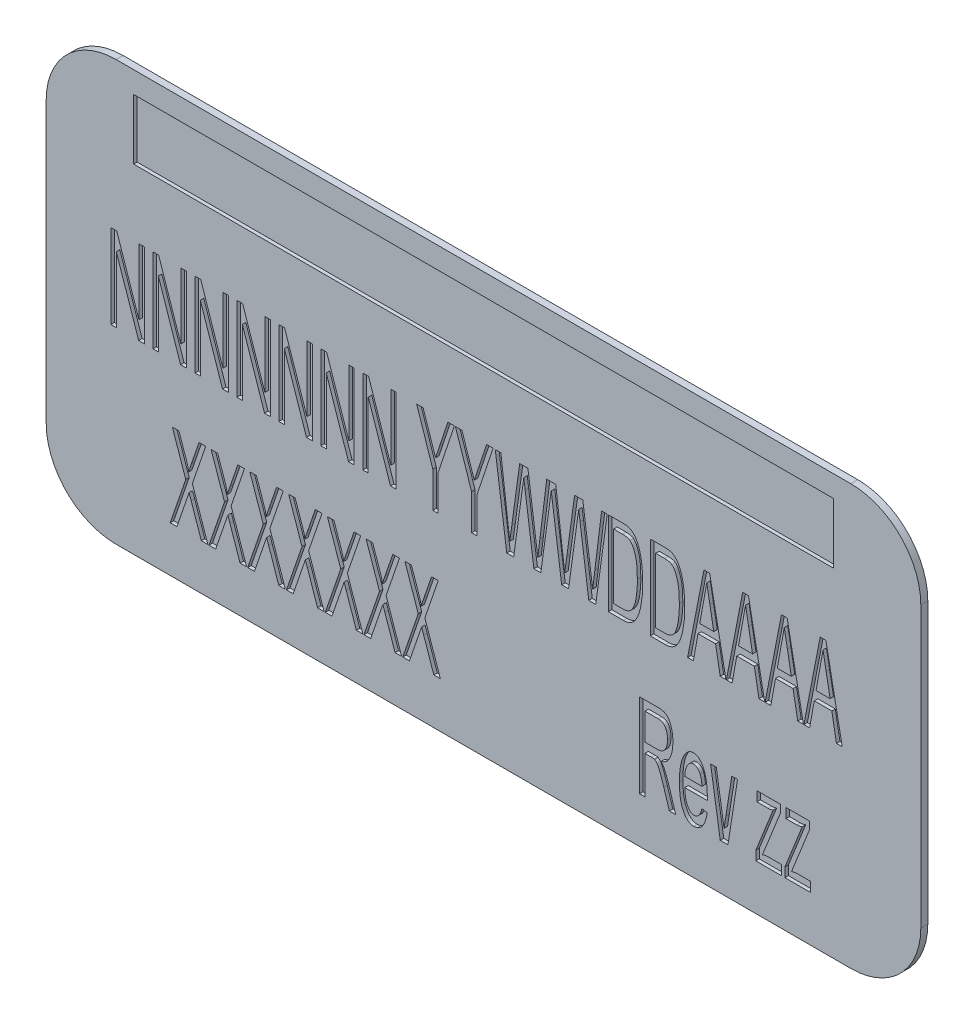
SolidWorks part; units mm, degrees
ref_plane "Face" through (0, 0, 0) normal (0, 0, 1) x (1, 0, 0)
ref_plane "Dessus" through (0, 0, 0) normal (0, 1, 0) x (1, 0, 0)
ref_plane "Droite" through (0, 0, 0) normal (1, 0, 0) x (0, 0, -1)
sketch "Esquisse1" plane through (0, 0, 0) normal (0, 0, 1) x (1, 0, 0)
  line L1 (-21.8488, 2.3382) -> (-0.8488, 2.3382)
  line L2 (-23.8488, 0.3382) -> (-23.8488, -7.6618)
  line L3 (-21.8488, -9.6618) -> (-0.8488, -9.6618)
  line L4 (1.1512, 0.3382) -> (1.1512, -7.6618)
  arc A0 (-0.8488, 2.3382) -> (1.1512, 0.3382) centre (-0.8488, 0.3382) cw
  arc A1 (1.1512, -7.6618) -> (-0.8488, -9.6618) centre (-0.8488, -7.6618) cw
  arc A2 (-21.8488, -9.6618) -> (-23.8488, -7.6618) centre (-21.8488, -7.6618) cw
  arc A3 (-23.8488, 0.3382) -> (-21.8488, 2.3382) centre (-21.8488, 0.3382) cw
  dimension "D3" = 2
  dimension "D1" = 25
  dimension "D2" = 12
extrude "Boss.-Extru.1" add sketch "Esquisse1" along normal blind 0.2
sketch "Esquisse2" plane through (0, 0, 0.2) normal (0, 0, 1) x (1, 0, 0)
  text T0 "NNNNNNN YYWWDDAAAA" font "Arial" height 2.4
extrude "Enlèv. mat.-Extru.1" cut sketch "Esquisse2" against normal blind 0.1
sketch "Esquisse8" plane through (0, 0, 0.2) normal (0, 0, 1) x (1, 0, 0)
  line L0 (-20.3043, -8.3563) -> (-1.1547, -8.3563) construction
  text T0 "XXXXXXX            Rev zz" font "Arial" height 2.4
extrude "Enlèv. mat.-Extru.2" cut sketch "Esquisse8" against normal blind 0.1
sketch "Esquisse10" plane through (0, 0, 0.2) normal (0, 0, 1) x (1, 0, 0)
  line L3 (-21.3488, 1.7251) -> (-1.3488, 1.7251)
  line L4 (-21.3488, 1.7251) -> (-21.3488, 0)
  line L5 (-21.3488, 0) -> (-1.3488, 0)
  line L6 (-1.3488, 1.7251) -> (-1.3488, 0)
extrude "Enlèv. mat.-Extru.3" cut sketch "Esquisse10" against normal blind 0.1
sketch "Esquisse11"
